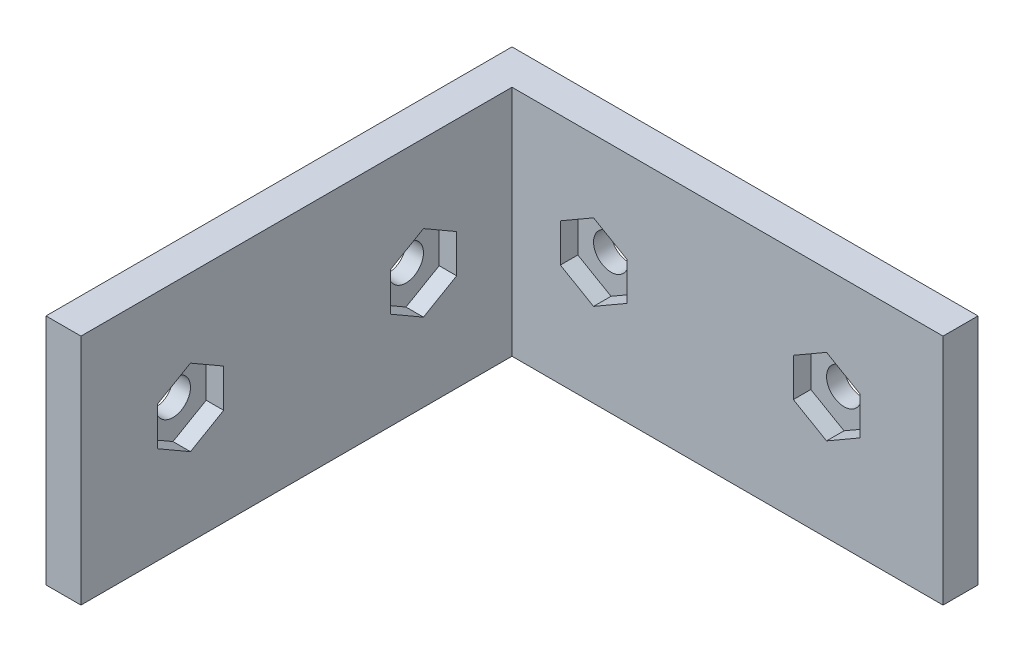
SolidWorks part; units mm, degrees
ref_plane "Plan de face" through (0, 0, 0) normal (0, 0, 1) x (1, 0, 0)
ref_plane "Plan de dessus" through (0, 0, 0) normal (0, 1, 0) x (1, 0, 0)
ref_plane "Plan de droite" through (0, 0, 0) normal (1, 0, 0) x (0, 0, -1)
sketch "Esquisse1" plane through (0, 0, 0) normal (0, 0, 1) x (1, 0, 0)
  line L1 (0, 0) -> (40, 0)
  line L2 (0, 0) -> (0, 20)
  line L3 (0, 20) -> (40, 20)
  line L4 (40, 0) -> (40, 20)
  dimension "D1" = 20
  dimension "D2" = 40
extrude "Boss.-Extru.1" add sketch "Esquisse1" along normal blind 3
sketch "Esquisse2" plane through (0, 0, 3) normal (0, 0, 1) x (1, 0, 0)
  line L0 (0, 20) -> (0, 0) construction
  line L1 (0, 0) -> (40, 0) construction
  circle A0 centre (10, 10.5) radius 1.5
  circle A1 centre (30, 10.5) radius 1.5
  dimension "D1" = 3
  dimension "D2" = 3
  dimension "D4" = 20
  dimension "D5" = 10.5
  dimension "D6" = 10.5
  dimension "D3" = 10
extrude "Enlèv. mat.-Extru.1" cut sketch "Esquisse2" against normal blind 3
sketch "Esquisse3" plane through (0, 0, 3) normal (0, 0, 1) x (1, 0, 0)
  line L0 (0, 0) -> (40, 0) construction
  line L1 (0, 20) -> (3, 20)
  line L2 (0, 20) -> (0, 0)
  line L3 (0, 0) -> (3, 0)
  line L4 (3, 20) -> (3, 0)
  dimension "D1" = 3
extrude "Boss.-Extru.2" add sketch "Esquisse3" along normal blind 37
sketch "Esquisse4" plane through (0, 0, 0) normal (-1, 0, 0) x (0, 0, 1)
  line L0 (0, 20) -> (0, 0) construction
  line L1 (40, 0) -> (0, 0) construction
  circle A0 centre (10.6, 10) radius 1.5
  circle A1 centre (30.6, 10) radius 1.5
  dimension "D1" = 3
  dimension "D2" = 3
  dimension "D3" = 20
  dimension "D4" = 10.6
  dimension "D5" = 10
  dimension "D6" = 10
extrude "Enlèv. mat.-Extru.2" cut sketch "Esquisse4" against normal blind 3
sketch "Esquisse5" plane through (3, 0, 0) normal (1, 0, 0) x (0, 0, -1)
  line L1 (-13.45, 8.3546) -> (-10.6, 6.7091)
  line L2 (-10.6, 6.7091) -> (-7.75, 8.3546)
  line L3 (-7.75, 8.3546) -> (-7.75, 11.6454)
  line L4 (-7.75, 11.6454) -> (-10.6, 13.2909)
  line L5 (-10.6, 13.2909) -> (-13.45, 11.6454)
  line L6 (-13.45, 11.6454) -> (-13.45, 8.3546)
  line L7 (-30.6, 6.7091) -> (-27.75, 8.3546)
  line L8 (-27.75, 8.3546) -> (-27.75, 11.6454)
  line L9 (-27.75, 11.6454) -> (-30.6, 13.2909)
  line L10 (-30.6, 13.2909) -> (-33.45, 11.6454)
  line L11 (-33.45, 11.6454) -> (-33.45, 8.3546)
  line L12 (-33.45, 8.3546) -> (-30.6, 6.7091)
  circle A0 centre (-10.6, 10) radius 2.85 construction
  circle A1 centre (-30.6, 10) radius 2.85 construction
  dimension "D1" = 5.7
  dimension "D2" = 5.7
extrude "Enlèv. mat.-Extru.3" cut sketch "Esquisse5" against normal blind 1.5
sketch "Esquisse6" plane through (0, 0, 3) normal (0, 0, 1) x (1, 0, 0)
  line L1 (27.15, 8.8546) -> (30, 7.2091)
  line L2 (30, 7.2091) -> (32.85, 8.8546)
  line L3 (32.85, 8.8546) -> (32.85, 12.1454)
  line L4 (32.85, 12.1454) -> (30, 13.7909)
  line L5 (30, 13.7909) -> (27.15, 12.1454)
  line L6 (27.15, 12.1454) -> (27.15, 8.8546)
  line L7 (10, 7.2091) -> (12.85, 8.8546)
  line L8 (12.85, 8.8546) -> (12.85, 12.1454)
  line L9 (12.85, 12.1454) -> (10, 13.7909)
  line L10 (10, 13.7909) -> (7.15, 12.1454)
  line L11 (7.15, 12.1454) -> (7.15, 8.8546)
  line L12 (7.15, 8.8546) -> (10, 7.2091)
  circle A0 centre (30, 10.5) radius 2.85 construction
  circle A1 centre (10, 10.5) radius 2.85 construction
  point P10 (31.425, 12.9682)
  dimension "D1" = 5.7
  dimension "D2" = 5.7
extrude "Enlèv. mat.-Extru.4" cut sketch "Esquisse6" against normal blind 1.5
